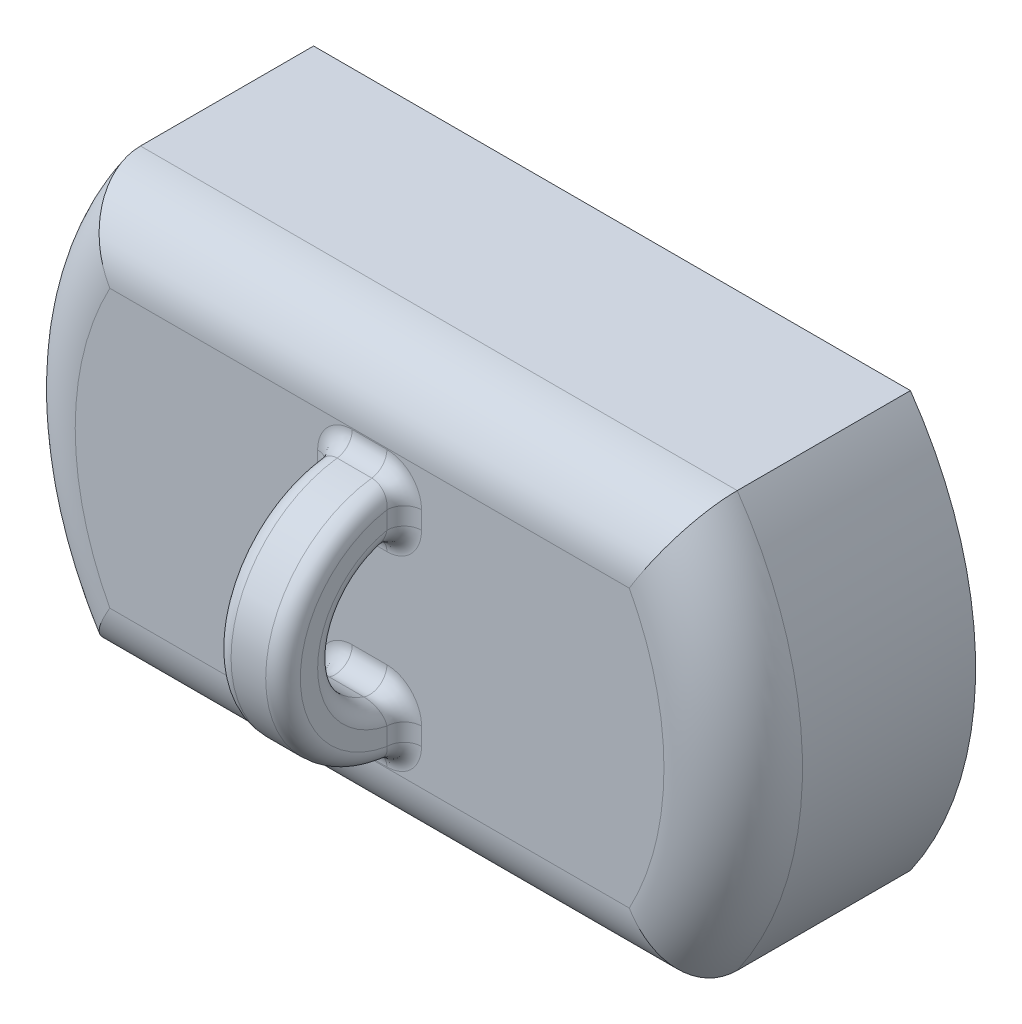
SolidWorks part; units mm, degrees
ref_plane "Plan de face" through (0, 0, 0) normal (0, 0, 1) x (1, 0, 0)
ref_plane "Plan de dessus" through (0, 0, 0) normal (0, 1, 0) x (1, 0, 0)
ref_plane "Plan de droite" through (0, 0, 0) normal (1, 0, 0) x (0, 0, -1)
sketch "Esquisse1" plane through (0, 0, 0) normal (0, 0, 1) x (1, 0, 0)
  line L0 (-8.6168, 6) -> (8.6168, 6)
  line L1 (-3.5, 2.5) -> (-8.5, 2.5) construction
  line L2 (-3.5, 2.5) -> (-3.5, -2.5) construction
  line L3 (-3.5, -2.5) -> (-8.5, -2.5) construction
  line L4 (-8.5, 2.5) -> (-8.5, -2.5) construction
  line L5 (8.5, 2.5) -> (3.5, 2.5) construction
  line L6 (8.5, 2.5) -> (8.5, -2.5) construction
  line L7 (8.5, -2.5) -> (3.5, -2.5) construction
  line L8 (3.5, 2.5) -> (3.5, -2.5) construction
  line L9 (5.225, 0) -> (-5.225, 0) construction
  line L10 (-8.6168, -6) -> (8.6168, -6)
  arc A0 (-8.6168, 6) -> (-8.6168, -6) centre (0, 0) ccw
  arc A1 (8.6168, -6) -> (8.6168, 6) centre (0, 0) ccw
  point P11 (-3.5, 0)
  point P13 (3.5, 0)
  dimension "D1" = 5
  dimension "D5" = 21
  dimension "D2" = 5
  dimension "D3" = 7
  dimension "D4" = 3.5
  dimension "D6" = 6
extrude "Boss.-Extru.1" add sketch "Esquisse1" along normal blind 7
sketch "Esquisse2" plane through (0, 0, 0) normal (0, 0, 1) x (1, 0, 0)
  line L0 (-3.5, 2.5) -> (-8.5, 2.5) construction
  line L1 (-8.5, 2.5) -> (-8.5, -2.5) construction
  line L2 (-3.5, -2.5) -> (-8.5, -2.5) construction
  line L3 (-3.5, 2.5) -> (-3.5, -2.5) construction
  line L4 (3.5, 2.5) -> (3.5, -2.5) construction
  line L5 (8.5, -2.5) -> (3.5, -2.5) construction
  line L6 (8.5, 2.5) -> (8.5, -2.5) construction
  line L7 (8.5, 2.5) -> (3.5, 2.5) construction
  line L8 (-3.5, 2.5) -> (-8.5, 2.5)
  line L9 (-8.5, 2.5) -> (-8.5, -2.5)
  line L10 (-3.5, -2.5) -> (-8.5, -2.5)
  line L11 (-3.5, 2.5) -> (-3.5, -2.5)
  line L12 (3.5, 2.5) -> (3.5, -2.5)
  line L13 (8.5, -2.5) -> (3.5, -2.5)
  line L14 (8.5, 2.5) -> (8.5, -2.5)
  line L15 (8.5, 2.5) -> (3.5, 2.5)
extrude "Enlèv. mat.-Extru.2" cut sketch "Esquisse2" along normal blind 5
fillet "Congé1" radius 2 4 edges at (0, 6, 7) (10.5, 0, 7) (0, -6, 7) (-10.5, 0, 7)
sketch "Esquisse3" plane through (0, 0, 0) normal (1, 0, 0) x (0, 0, -1)
  line L0 (-7, 4) -> (-7, -4) construction
  line L1 (-7, -3.5) -> (-7, -2)
  line L2 (-7, 3.5) -> (-7, 2)
  arc A0 (-7, 2) -> (-7, -2) centre (-7, 0) ccw
  arc A1 (-7, 3.5) -> (-7, -3.5) centre (-7, 0) ccw
  point P8 (0, 0)
  dimension "D1" = 2
  dimension "D2" = 1.5
extrude "Boss.-Extru.2" add sketch "Esquisse3" along normal mid plane 2
fillet "Congé4" radius 0.5 12 edges at (0, -3.5, 7) (0, 3.5, 7) (-1, -2.75, 7) (-1, 2.75, 7) (1, 2.75, 7) (1, -2.75, 7) (0, 2, 7) (0, -2, 7) (1, 0, 9) (1, 0, 10.5) (-1, 0, 10.5) (-1, 0, 9)
